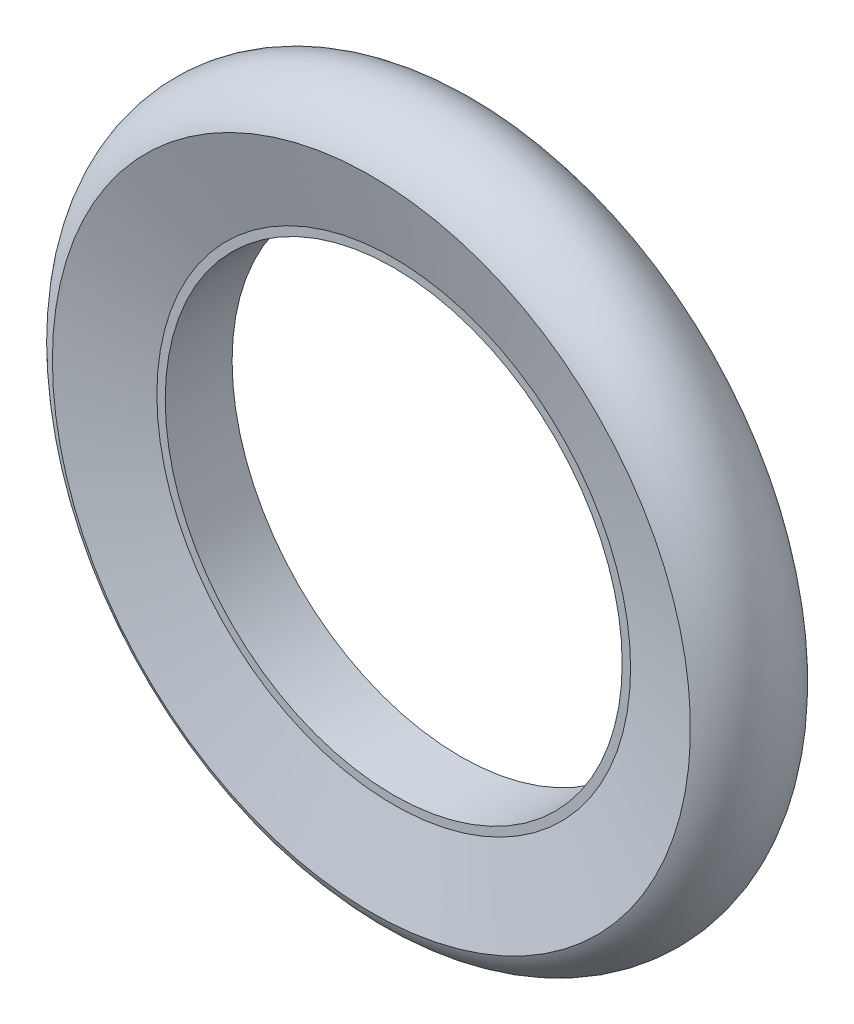
SolidWorks part; units mm, degrees
ref_plane "Спереди" through (0, 0, 0) normal (0, 0, 1) x (1, 0, 0)
ref_plane "Сверху" through (0, 0, 0) normal (0, 1, 0) x (1, 0, 0)
ref_plane "Справа" through (0, 0, 0) normal (1, 0, 0) x (0, 0, -1)
other "Configuration Table"
sketch "Sketch1" plane through (0, 0, 0) normal (0, 1, 0) x (1, 0, 0)
  line L1 (-291.9341, 0) -> (14.6359, 0) construction
  line L2 (0, 36.4643) -> (0, -49.4873) construction
  line L3 (-170, -24) -> (-229, -40)
  line L4 (-170, 24) -> (-229, 40)
  line L5 (-229, -40) -> (-229, 40) construction
  line L6 (-170, -24) -> (-164, -24)
  line L7 (-164, -24) -> (-164, 24)
  line L8 (-164, 24) -> (-170, 24)
  line L9 (-170, -24) -> (-170, 24) construction
  arc A1 (-229, -40) -> (-229, 40) centre (-211.2308, 0) cw
  dimension "D2" = 48
  dimension "D4" = 85
  dimension "D7" = 510
  dimension "D8" = 43.7692
  dimension "D1" = 6
  dimension "D3" = 164
  dimension "D5" = 26
  dimension "D6" = 80
revolve "Revolve1" add sketch "Sketch1" angle 360 about L2
equation "\"65.00mmф\"=65"
